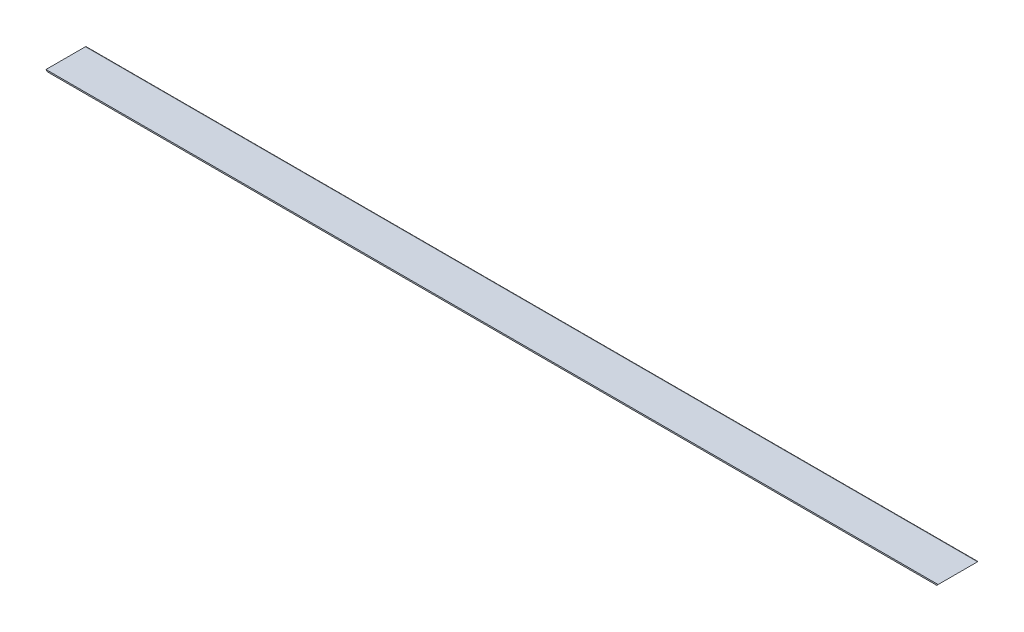
SolidWorks part; units mm, degrees
ref_plane "Front Plane" through (0, 0, 0) normal (0, 0, 1) x (1, 0, 0)
ref_plane "Top Plane" through (0, 0, 0) normal (0, 1, 0) x (1, 0, 0)
ref_plane "Right Plane" through (0, 0, 0) normal (1, 0, 0) x (0, 0, -1)
sketch "Sketch1" plane through (0, 0, 0) normal (1, 0, 0) x (0, 0, -1)
  line L0 (0, 0) -> (88, 0)
  line L1 (88, 0) -> (88, -88)
  line L2 (0, -3) -> (85, -3)
  line L3 (85, -3) -> (85, -88)
  line L4 (85, -88) -> (88, -88)
  line L5 (0, 0) -> (0, -3)
  dimension "D1" = 88
  dimension "D2" = 88
  dimension "D3" = 3
extrude "Boss-Extrude1" add sketch "Sketch1" along normal blind 1930
fillet "Fillet1" radius 3 2 edges at (965, -3, -85) (965, 0, -88)
sketch "Sketch2" plane through (0, 0, -88) normal (0, 0, -1) x (-1, 0, 0)
  line L0 (0, 0) -> (-88, -88)
  line L1 (-1930, -88) -> (0, -88) construction
  line L2 (-88, -88) -> (0, -88)
  line L3 (0, -88) -> (0, 0)
  dimension "D1" = 45
extrude "Cut-Extrude1" cut sketch "Sketch2" against normal blind 88
sketch "Sketch3" plane through (0, 0, -88) normal (0, 0, -1) x (-1, 0, 0)
  line L0 (-1930, 0) -> (-1842, -88)
  line L1 (-1930, -88) -> (-88, -88) construction
  line L2 (-1842, -88) -> (-1930, -88)
  line L3 (-1930, -88) -> (-1930, 0)
  dimension "D1" = 45
extrude "Cut-Extrude2" cut sketch "Sketch3" against normal blind 88
equation "\"D1@Boss-Extrude1\" = \"boxWidth\""
equation "\"CarBeamWidth\"=700.0"
equation "\"WheelWidth\"=650.0"
equation "\"Wheel_FrontBoxDistance\"=1390.0"
equation "\"boxLength\"=5100.0"
equation "\"boxWidth\"=1930.0"
equation "\"MetalSheet_3mm_length\"=5030.0"
equation "\"MetalSheet_3mm_width\"=1923.0"
equation "\"MetalSheet_3mm_FloorCut_L_length\"=1764.0"
equation "\"MetalSheet_3mm_FloorCut_L_disdance\"=1665.0"
equation "\"MetalSheet_3mm_FloorCut_R_length\"=1764.0"
equation "\"MetalSheet_3mm_FloorCut_R_disdance\"=1665.0"
equation "\"indoorHeight\"=1940.0"
equation "\"indoorHeight_para\"=25.0"
equation "\"rearLightHeight_para\"=265.0"
equation "\"haveDoor_R\"=1"
equation "\"side_door_bottom_R_3mm_length\"=1934.0"
equation "\"side_door_bottom_R_3mm_toFrontDistance\"=1583.0"
equation "\"1Bar_Side_RF_3mm_length\"=1493.0"
equation "\"1Bar_Side_RB_3mm_length\"=1493.0"
equation "\"DoorSeparator_RF_3mm_withHinge_toFrontDistance\"=1673.0"
equation "\"DoorSeparator_RF_3mm_withHinge_exist\"=1"
equation "\"DoorSeparator_RB_3mm_withHinge_toFrontDistance\"=3427.0"
equation "\"DoorSeparator_RB_3mm_withHinge_exist\"=1"
equation "\"Door_R1_L_open_Single_toFrontDistance\"=2547.5"
equation "\"Door_R1_L_open_Single_exist\"=1"
equation "\"door_base_long7_R1_L_open_Single_height\"=1890.0"
equation "\"door_base_short7_R1_L_open_Single_height\"=1890.0"
equation "\"door_base_short7_R1_L_open_Single_width\"=864"
equation "\"Door_R1_R_open_Single_toFrontDistance\"=3422.0"
equation "\"Door_R1_R_open_Single_exist\"=1"
equation "\"door_base_long7_R1_R_open_Single_height\"=1890.0"
equation "\"door_base_short7_R1_R_open_Single_height\"=1890.0"
equation "\"door_base_short7_R1_R_open_Single_width\"=864"
equation "\"x\"=66.0"
equation "\"door_base_double_BL_height\"=1890.0"
equation "\"door_base_short7_BL_Single_height\"=1890.0"
equation "\"door_base_short7_BL_Single_width\"=864"
equation "\"door_base_long7_BR_Single_height\"=1890.0"
equation "\"door_base_short7_BR_Single_height\"=1890.0"
equation "\"door_base_short7_BR_Single_width\"=864"
equation "\"da\"=62.0"
equation "\"SquareTube_length\"=1923.0"
equation "\"channelSteel_length\"=5030.0"
equation "\"SquareTube_inFront_AvgDistance\"=285.0"
equation "\"SquareTube_inFront_TotalCount\"=5"
equation "\"SquareTube_inFront1_cutDepth50_R\"=0.5"
equation "\"SquareTube_inFront1_cutDepth50_L\"=0.5"
equation "\"SquareTube_inFront2_cutDepth50_R\"=0.5"
equation "\"SquareTube_inFront2_cutDepth50_L\"=0.5"
equation "\"SquareTube_inFront3_cutDepth50_R\"=0.5"
equation "\"SquareTube_inFront3_cutDepth50_L\"=0.5"
equation "\"SquareTube_inFront4_cutDepth50_R\"=0.5"
equation "\"SquareTube_inFront4_cutDepth50_L\"=0.5"
equation "\"SquareTube_inFront5_cutDepth50_R\"=50"
equation "\"SquareTube_inFront5_cutDepth50_L\"=50"
equation "\"SquareTube_inFront6_cutDepth50_R\"=50"
equation "\"SquareTube_inFront6_cutDepth50_L\"=50"
equation "\"SquareTube_inFront7_cutDepth50_R\"=50"
equation "\"SquareTube_inFront7_cutDepth50_L\"=50"
equation "\"SquareTube_inFront8_cutDepth50_R\"=50"
equation "\"SquareTube_inFront8_cutDepth50_L\"=50"
equation "\"SquareTube_inFront9_cutDepth50_R\"=50"
equation "\"SquareTube_inFront9_cutDepth50_L\"=50"
equation "\"SquareTube_inFront10_cutDepth50_R\"=50"
equation "\"SquareTube_inFront10_cutDepth50_L\"=50"
equation "\"SquareTube_inFront11_cutDepth50_R\"=50"
equation "\"SquareTube_inFront11_cutDepth50_L\"=50"
equation "\"SquareTube_inFront12_cutDepth50_R\"=50"
equation "\"SquareTube_inFront12_cutDepth50_L\"=50"
equation "\"SquareTube_inFront13_cutDepth50_R\"=50"
equation "\"SquareTube_inFront13_cutDepth50_L\"=50"
equation "\"SquareTube_inFront14_cutDepth50_R\"=50"
equation "\"SquareTube_inFront14_cutDepth50_L\"=50"
equation "\"SquareTube_inBack_AvgDistance\"=333.125"
equation "\"SquareTube_inBack_TotalCount\"=9"
equation "\"SquareTube_inBack1_cutDepth50_R\"=50"
equation "\"SquareTube_inBack1_cutDepth50_L\"=50"
equation "\"SquareTube_inBack2_cutDepth50_R\"=50"
equation "\"SquareTube_inBack2_cutDepth50_L\"=50"
equation "\"SquareTube_inBack3_cutDepth50_R\"=50"
equation "\"SquareTube_inBack3_cutDepth50_L\"=50"
equation "\"SquareTube_inBack4_cutDepth50_R\"=50"
equation "\"SquareTube_inBack4_cutDepth50_L\"=50"
equation "\"SquareTube_inBack5_cutDepth50_R\"=50"
equation "\"SquareTube_inBack5_cutDepth50_L\"=50"
equation "\"SquareTube_inBack6_cutDepth50_R\"=0.5"
equation "\"SquareTube_inBack6_cutDepth50_L\"=0.5"
equation "\"SquareTube_inBack7_cutDepth50_R\"=0.5"
equation "\"SquareTube_inBack7_cutDepth50_L\"=0.5"
equation "\"SquareTube_inBack8_cutDepth50_R\"=0.5"
equation "\"SquareTube_inBack8_cutDepth50_L\"=0.5"
